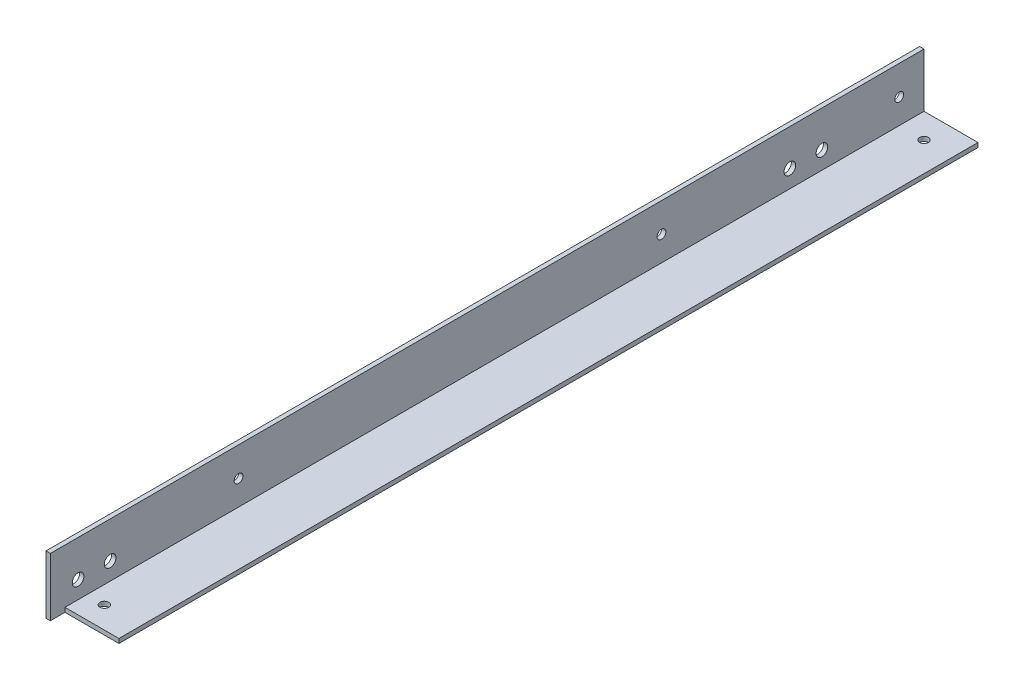
SolidWorks part; units mm, degrees
ref_plane "Plan de face" through (0, 0, 0) normal (0, 0, 1) x (1, 0, 0)
ref_plane "Plan de dessus" through (0, 0, 0) normal (0, 1, 0) x (1, 0, 0)
ref_plane "Plan de droite" through (0, 0, 0) normal (1, 0, 0) x (0, 0, -1)
sketch "Esquisse1" plane through (0, 0, 0) normal (0, 0, 1) x (1, 0, 0)
  line L0 (-17.4317, 4.7734) -> (-17.4317, -15.2266)
  line L1 (-17.4317, -15.2266) -> (2.5683, -15.2266)
  line L2 (2.5683, -15.2266) -> (2.5683, -13.7266)
  line L3 (2.5683, -13.7266) -> (-15.9317, -13.7266)
  line L4 (-15.9317, -13.7266) -> (-15.9317, 4.7734)
  line L5 (-15.9317, 4.7734) -> (-17.4317, 4.7734)
  dimension "D1" = 1.5
  dimension "D2" = 1.5
  dimension "D3" = 20
  dimension "D4" = 20
extrude "Extrusion1" add sketch "Esquisse1" along normal blind 294.5
sketch "Esquisse2" plane through (0, -13.7266, 0) normal (0, 1, 0) x (-1, 0, 0)
  line L0 (-2.5683, 294.5) -> (-2.5683, 0) construction
  line L2 (-2.5683, 0) -> (15.9317, 0) construction
  circle A1 centre (7.4317, 8.5) radius 1.5
  dimension "D1" = 8.5
  dimension "D4" = 10
extrude "Extrusion2" cut sketch "Esquisse2" against normal blind 300
sketch "Esquisse3" plane through (-15.9317, 0, 0) normal (1, 0, 0) x (0, 0, -1)
  line L0 (-321.5, -5.2266) -> (-8.5, -5.2266) construction
  line L1 (-294.5, -13.7266) -> (-294.5, 4.7734) construction
  line L2 (0, -13.7266) -> (0, 4.7734) construction
  line L3 (-294.5, 4.7734) -> (0, 4.7734) construction
  line L4 (-290, -7.7266) -> (-279, -7.7266) construction
  line L5 (-46, -7.7266) -> (-35, -7.7266) construction
  line L6 (0, -13.7266) -> (0, 4.7734) construction
  line L7 (-294.5, -13.7266) -> (0, -13.7266) construction
  circle A1 centre (-8.5, -5.2266) radius 1.5
  circle A2 centre (-35, -7.7266) radius 2
  circle A3 centre (-46, -7.7266) radius 2
  circle A4 centre (-290, -7.7266) radius 2
  circle A5 centre (-279, -7.7266) radius 2
  circle A6 centre (-235, -5.2266) radius 1.5
  circle A7 centre (-90, -5.2266) radius 1.5
  dimension "D4" = 11
  dimension "D9" = 6
  dimension "D6" = 11
  dimension "D8" = 6
  dimension "D10" = 59.5
  dimension "D2" = 8.5
  dimension "D3" = 10
  dimension "D5" = 4.5
  dimension "D7" = 35
  dimension "D11" = 90
extrude "Extrusion3" cut sketch "Esquisse3" against normal blind 300
sketch "Esquisse4" plane through (0, 0, 294.5) normal (0, 0, 1) x (1, 0, 0)
  line L0 (-17.4317, -15.2266) -> (2.5683, -15.2266) construction
  line L1 (-17.4317, 4.7734) -> (-15.9317, 4.7734)
  line L2 (-17.4317, 4.7734) -> (-17.4317, -15.2266)
  line L3 (-17.4317, -15.2266) -> (-15.9317, -15.2266)
  line L4 (-15.9317, 4.7734) -> (-15.9317, -15.2266)
  dimension "D1" = 1.5
extrude "Extrusion4" add sketch "Esquisse4" along normal blind 5
sketch "Esquisse5" plane through (0, -15.2266, 0) normal (0, -1, 0) x (1, 0, 0)
  line L0 (-17.4317, 299.5) -> (-17.4317, 0) construction
  line L1 (-15.9317, 294.5) -> (2.5683, 294.5) construction
  circle A0 centre (-9.9317, 287) radius 1.5
  dimension "D1" = 7.5
  dimension "D2" = 7.5
extrude "Extrusion5" cut sketch "Esquisse5" against normal blind 5
